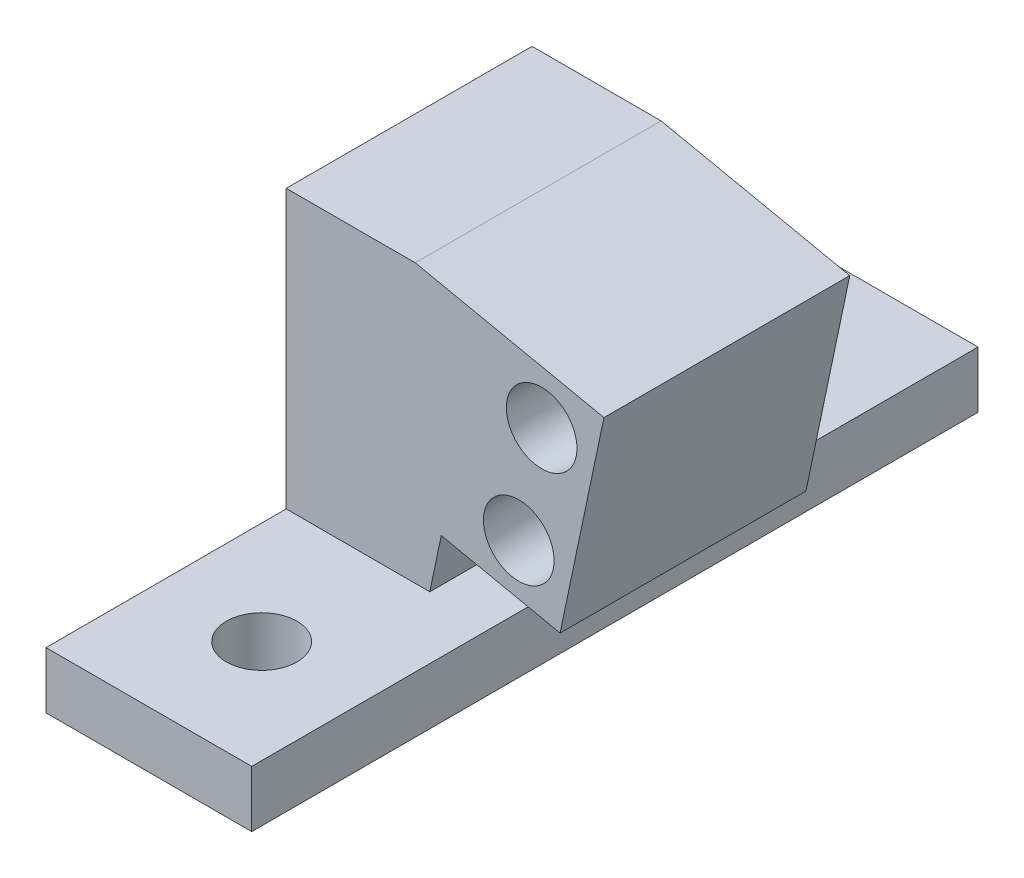
SolidWorks part; units mm, degrees
ref_plane "Front Plane" through (0, 0, 0) normal (0, 0, 1) x (1, 0, 0)
ref_plane "Top Plane" through (0, 0, 0) normal (0, 1, 0) x (1, 0, 0)
ref_plane "Right Plane" through (0, 0, 0) normal (1, 0, 0) x (0, 0, -1)
sketch "Sketch2" plane through (0, 0, 0) normal (0, 0, 1) x (1, 0, 0)
  line L0 (-629.4563, 228.6083) -> (-646.4173, 232.1744)
  line L1 (-626.309, 227.9466) -> (-640.2031, 230.8679) construction
  line L2 (-646.4173, 232.1744) -> (-650.3578, 213.4325)
  line L3 (-650.3578, 213.4325) -> (-633.3967, 209.8665)
  line L4 (-627.1923, 208.562) -> (-644.038, 212.1038) construction
  line L5 (-633.3967, 209.8665) -> (-629.4563, 228.6083)
  circle A0 centre (-637.1112, 215.214) radius 3.175 construction
  circle A1 centre (-635.0536, 225) radius 3.175 construction
  circle A2 centre (-637.1112, 215.214) radius 3.175
  circle A3 centre (-635.0536, 225) radius 3.175
  circle A4 centre (-637.1112, 215.214) radius 3.175
  circle A5 centre (-635.0536, 225) radius 3.175
  circle M5 centre (-637.1112, 215.214) radius 3.175
  line M6 (-610.5669, 224.6368) -> (-640.2031, 230.8679)
  arc M7 (-640.2031, 230.8679) -> (-641.8455, 221.1503) centre (-635.0536, 225) ccw
  arc M8 (-641.8455, 221.1503) -> (-644.038, 212.1038) centre (-637.1112, 215.214) ccw
  line M9 (-644.038, 212.1038) -> (-609.6489, 204.8735)
  circle M13 centre (-635.0536, 225) radius 3.175
  dimension "D1" = 19.1516
  dimension "D2" = 17.3318
  dimension "D3" = 6.35
extrude "Boss-Extrude1" add sketch "Sketch2" along normal up to surface (2953.4037 mm away) contours L5 M9 M6 M7 M8 M13 M5 | L2 L3 L0 M8 M7
sketch "Sketch3" plane through (15.4424, 73.4471, 0) normal (-0.2058, -0.9786, 0) x (0.9786, -0.2058, 0)
  line L1 (-680.3571, 22.098) -> (-673.9421, 22.098)
  line L2 (-663.0252, 22.098) -> (-680.3571, 22.098) construction
  line L3 (-673.9421, 22.098) -> (-673.9421, 0)
  line L5 (-680.3571, 0) -> (-680.3571, 22.098)
  line L6 (-680.3571, 0) -> (-663.0252, 0) construction
  line L7 (-673.9421, 0) -> (-680.3571, 0)
  dimension "D1" = 6.4149
extrude "Boss-Extrude2" add sketch "Sketch3" along normal blind 6.35 contours L7 L5 L1 L3
ref_plane "Plane2" through (0, 207.2184, 0) normal (0, 1, 0) x (1, 0, 0)
sketch "Sketch5" plane through (0, 207.2184, 0) normal (0, 1, 0) x (1, 0, 0)
  line L0 (-615.5566, -5.7353) -> (-738.2448, -200.0271) construction
  line L1 (-658.0143, 21.59) -> (-639.5224, 21.59)
  line L2 (-658.0143, 21.59) -> (-658.0143, -43.688)
  line L3 (-658.0143, -43.688) -> (-639.5224, -43.688)
  line L4 (-639.5224, 21.59) -> (-639.5224, -43.688)
  circle A0 centre (-648.7934, -33.528) radius 3.175
  circle A1 centre (-648.7934, 11.43) radius 3.175
  dimension "D4" = 9.271
  dimension "D7" = 6.35
  dimension "D8" = 6.35
  dimension "D1" = 21.59
  dimension "D2" = 21.59
  dimension "D3" = 6.35
  dimension "D5" = 10.16
  dimension "D6" = 9.271
  dimension "D9" = 10.16
extrude "Boss-Extrude4" add sketch "Sketch5" against normal blind 5.08
sketch "Sketch7" plane through (-658.0143, 0, 0) normal (-1, 0, 0) x (0, 0, 1)
  line L1 (0, 207.2184) -> (22.098, 207.2184)
  line L2 (0, 207.2184) -> (0, 232.1744)
  line L3 (0, 232.1744) -> (22.098, 232.1744)
  line L4 (22.098, 207.2184) -> (22.098, 232.1744)
extrude "Boss-Extrude7" add sketch "Sketch7" against normal up to surface (6.35 mm away)
